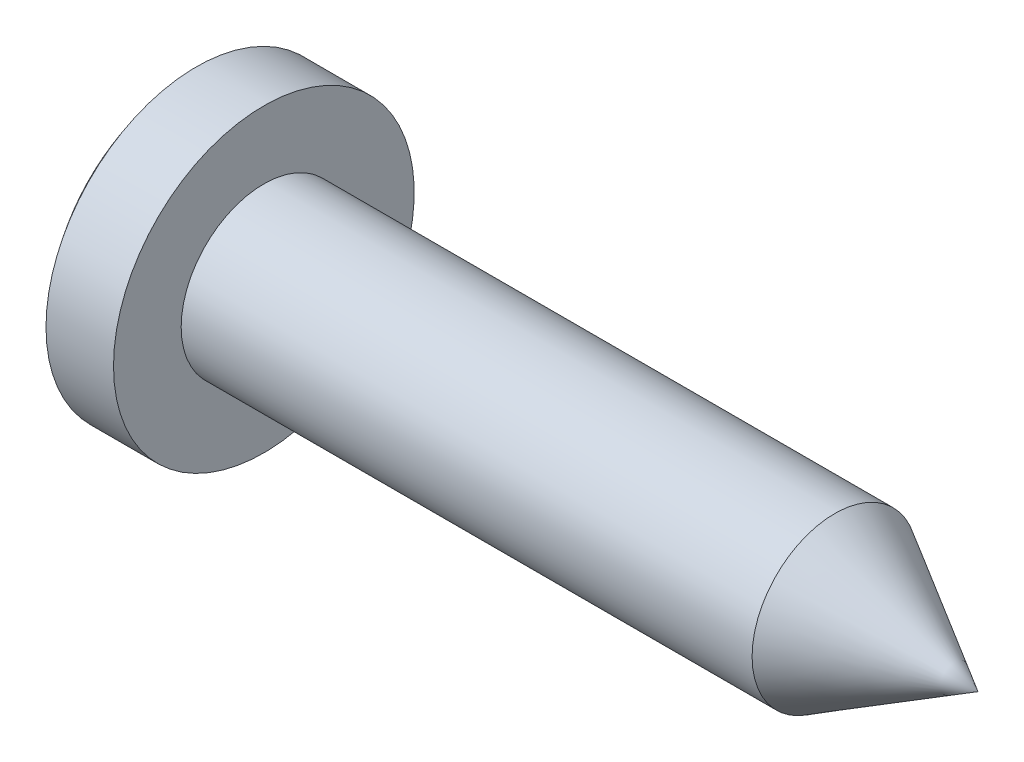
SolidWorks part; units mm, degrees
ref_plane "Front Plane" through (0, 0, 0) normal (0, 0, 1) x (1, 0, 0)
ref_plane "Top Plane" through (0, 0, 0) normal (0, 1, 0) x (1, 0, 0)
ref_plane "Right Plane" through (0, 0, 0) normal (1, 0, 0) x (0, 0, -1)
sketch "Sketch1" plane through (0, 0, 0) normal (0, 0, 1) x (1, 0, 0)
  line L0 (0, 0) -> (5.2282, 0) construction
  line L2 (0, 2) -> (-0.898, 2)
  line L3 (-1.6, 0) -> (-1.6, -0.7496) construction
  line L4 (-1.6, 0) -> (9.5, 0)
  line L5 (0, 1.1) -> (9.5, 1.1)
  line L6 (9.5, 1.1) -> (9.5, 0)
  line L7 (0, 1.1) -> (0, 2)
  arc A0 (-0.898, 2) -> (-1.6, 0) centre (1.6, 0) ccw
  dimension "rf" = 3.2
  dimension "Dk" = 4
  dimension "K" = 1.6
  dimension "d" = 2.2
  dimension "l" = 9.5
revolve "Revolve1" add sketch "Sketch1" angle 360 about L0
cosmetic thread "ThreadCosmetic" [suppressed] parameters "D1"=9.28, "D2"=1.63
chamfer "Chamfer1" distance 0.22 angle 60 1 edges at (9.5, 0, 1.1)
sketch "Sketch5" plane through (0, 0, 0) normal (0, 0, 1) x (1, 0, 0)
  line L0 (0.7155, 0.815) -> (0.2445, 0.815)
  line L1 (0.2445, 0.815) -> (0.08, 1.1)
  line L2 (0.7155, 0.815) -> (0.88, 1.1)
  line L3 (0.08, 1.1) -> (0.08, 1.35)
  line L4 (0.88, 1.1) -> (0.88, 1.35)
  line L5 (0.08, 1.35) -> (0.88, 1.35)
  line L6 (0.48, 0.815) -> (0.48, 0) construction
  line L7 (0, 0) -> (7.3035, 0) construction
  line L9 (9.1189, 1.1) -> (0, 1.1) construction
  line L12 (0, -1.1) -> (0, 1.1) construction
  dimension "D2" = 60
  dimension "D3" = 0.25
  dimension "advance" = 0.8
  dimension "minordia" = 1.63
  dimension "threadstart" = 0.48
revolve "ThreadSchematic" [suppressed] cut sketch "Sketch5" angle 360 about L7
pattern_linear "ThdSchPat" [suppressed] count 12 spacing 0.8 along (1, 0, 0)
sketch "Sketch2" plane through (0, 0, 0) normal (0, 0, 1) x (1, 0, 0)
  line L0 (0, 0) -> (5.7679, 0) construction
  line L1 (9.5, 0) -> (7.5947, 1.1)
  line L3 (9.5, 1.1) -> (9.5, 0) construction
  line L4 (7.5947, 1.1) -> (7.5947, 1.2)
  line L5 (7.5947, 1.2) -> (9.6, 1.2)
  line L6 (9.6, 1.2) -> (9.6, 0)
  line L7 (9.6, 0) -> (9.5, 0)
  point P9 (0, 1.1)
  dimension "D1" = 30
  dimension "D2" = 0.1
  dimension "D3" = 0.1
revolve "EndCone" cut sketch "Sketch2" angle 360 about L0
ref_plane "Plane4" through (-1.6, 0, 0) normal (1, 0, 0) x (0, 0, -1)
sketch "Sketch3" plane through (-1.6, 0, 0) normal (1, 0, 0) x (0, 0, -1)
  line L0 (0, 2.343) -> (0, -2.4842) construction
  line L1 (2.7661, 0) -> (-3.4558, 0) construction
  line L2 (-0.2375, 0.95) -> (0.2375, 0.95)
  line L3 (0.2375, 0.95) -> (0.1425, 0.57)
  line L4 (0, 0) -> (1.9578, 1.9578) construction
  line L5 (0.1425, 0.57) -> (0.299, 0.299)
  line L6 (0.1425, 0.57) -> (0, 0) construction
  line L7 (-0.1425, 0.57) -> (-0.299, 0.299)
  line L8 (-0.2375, 0.95) -> (-0.1425, 0.57)
  line L9 (0.95, 0.2375) -> (0.95, -0.2375)
  line L10 (0.95, -0.2375) -> (0.57, -0.1425)
  line L11 (0.57, -0.1425) -> (0.299, -0.299)
  line L12 (0.57, 0.1425) -> (0.299, 0.299)
  line L13 (0.95, 0.2375) -> (0.57, 0.1425)
  line L14 (0.2375, -0.95) -> (-0.2375, -0.95)
  line L15 (-0.2375, -0.95) -> (-0.1425, -0.57)
  line L16 (-0.1425, -0.57) -> (-0.299, -0.299)
  line L17 (0.1425, -0.57) -> (0.299, -0.299)
  line L18 (0.2375, -0.95) -> (0.1425, -0.57)
  line L19 (-0.95, -0.2375) -> (-0.95, 0.2375)
  line L20 (-0.95, 0.2375) -> (-0.57, 0.1425)
  line L21 (-0.57, 0.1425) -> (-0.299, 0.299)
  line L22 (-0.57, -0.1425) -> (-0.299, -0.299)
  line L23 (-0.95, -0.2375) -> (-0.57, -0.1425)
  point P14 (0, 0.95)
  point P23 (0.95, 0)
  point P30 (0, -0.95)
  point P37 (-0.95, 0)
  dimension "D1" = 45
  dimension "m" = 1.9
  dimension "D3" = 0.475
  dimension "D4" = 75
  dimension "D5" = 1.14
extrude "Cut-Extrude1" cut sketch "Sketch3" along normal blind 0.85 draft 6
equation "\"D1@Chamfer1\" = \"d@Sketch1\"/10"
equation "\"D1@ThreadCosmetic\" = \"l@Sketch1\" - \"D1@Chamfer1\""
equation "\"minordia@Sketch5\" = \"D2@ThreadCosmetic\""
equation "\"D1@Plane4\" = \"K@Sketch1\""
equation "\"D5@Sketch3\" = \"m@Sketch3\" * 3 / 5"
equation "\"D3@Sketch3\" = \"m@Sketch3\" / 4"
equation "\"threadstart@Sketch5\" = \"advance@Sketch5\"*0.6"
equation "\"D1@ThdSchPat\" = int((\"l@Sketch1\"/\"advance@Sketch5\") + 0.999)"
equation "\"D3@ThdSchPat\" = \"advance@Sketch5\""
